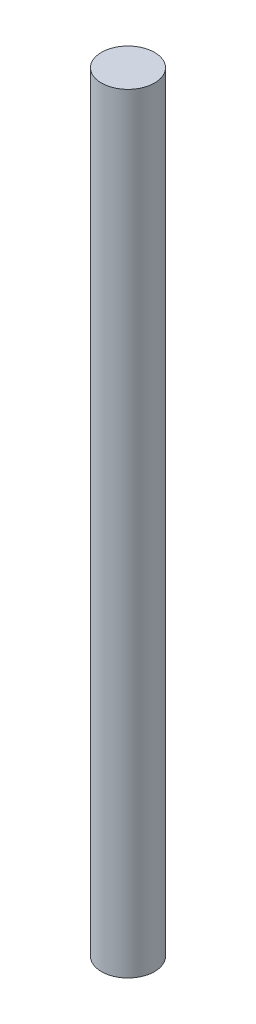
SolidWorks part; units mm, degrees
ref_plane "Front Plane" through (0, 0, 0) normal (0, 0, 1) x (1, 0, 0)
ref_plane "Top Plane" through (0, 0, 0) normal (0, 1, 0) x (1, 0, 0)
ref_plane "Right Plane" through (0, 0, 0) normal (1, 0, 0) x (0, 0, -1)
sketch "Sketch1" plane through (0, 0, 0) normal (0, 1, 0) x (1, 0, 0)
  circle A0 centre (0, 0) radius 1.5875
  dimension "D1" = 3.175
extrude "Boss-Extrude1" add sketch "Sketch1" along normal blind 46
